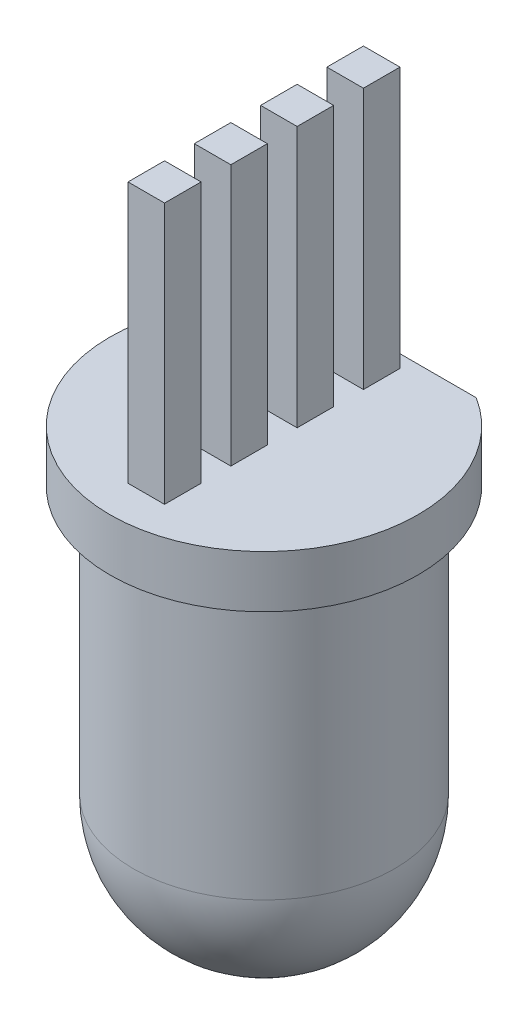
SolidWorks part; units mm, degrees
ref_plane "Plan de face" through (0, 0, 0) normal (0, 0, 1) x (1, 0, 0)
ref_plane "Plan de dessus" through (0, 0, 0) normal (0, 1, 0) x (1, 0, 0)
ref_plane "Plan de droite" through (0, 0, 0) normal (1, 0, 0) x (0, 0, -1)
sketch "Esquisse1" plane through (0, 0, 0) normal (0, 0, 1) x (1, 0, 0)
  line L0 (2.5, 7.6) -> (2.5, 2.5)
  line L1 (2.5, 7.6) -> (2.95, 7.6)
  line L2 (2.95, 7.6) -> (2.95, 8.6)
  line L3 (2.95, 8.6) -> (0, 8.6)
  line L4 (0, 0) -> (0, 10.615) construction
  line L5 (0, 0) -> (0, 8.6)
  arc A0 (2.5, 2.5) -> (0, 0) centre (0, 2.5) cw
  dimension "D1" = 2.5
  dimension "D2" = 7.6
  dimension "D3" = 90
  dimension "D4" = 0.45
  dimension "D5" = 1
  dimension "D6" = 5.9
revolve "Révolution1" add sketch "Esquisse1" angle 360 about L4
sketch "Esquisse2" plane through (0, 7.6, 0) normal (0, -1, 0) x (-1, 0, 0)
  line L0 (2.0316, 2.5) -> (-2.1192, 2.5)
  line L1 (2.0316, 2.5) -> (-0.3043, 5.4158)
  line L2 (-0.3043, 5.4158) -> (-2.1192, 2.5)
  circle A0 centre (0, 0) radius 2.5 construction
extrude "Enlèv. mat.-Extru.1" cut sketch "Esquisse2" against normal up to next
sketch "Esquisse3" plane through (0, 8.6, 0) normal (0, 1, 0) x (1, 0, 0)
  line L0 (-0.35, 2.255) -> (0.35, 2.255)
  line L1 (0.35, 2.255) -> (0.35, 1.555)
  line L2 (0.35, 1.555) -> (-0.35, 1.555)
  line L3 (-0.35, 1.555) -> (-0.35, 2.255)
  line L4 (-0.35, -0.985) -> (0.35, -0.985)
  line L5 (0.35, -0.985) -> (0.35, -0.285)
  line L6 (0.35, -0.285) -> (-0.35, -0.285)
  line L7 (-0.35, -0.285) -> (-0.35, -0.985)
  line L8 (-0.35, -1.555) -> (0.35, -1.555)
  line L9 (0.35, -1.555) -> (0.35, -2.255)
  line L10 (0.35, -2.255) -> (-0.35, -2.255)
  line L11 (-0.35, -2.255) -> (-0.35, -1.555)
  line L12 (-0.35, 0.985) -> (0.35, 0.985)
  line L13 (0.35, 0.985) -> (0.35, 0.285)
  line L14 (0.35, 0.285) -> (-0.35, 0.285)
  line L15 (-0.35, 0.285) -> (-0.35, 0.985)
  line L16 (0, 2.8041) -> (0, -3.2431) construction
  dimension "D1" = 0.7
  dimension "D2" = 0.7
  dimension "D3" = 0.35
  dimension "D4" = 0.35
  dimension "D5" = 0.35
  dimension "D6" = 0.7
  dimension "D7" = 0.7
  dimension "D8" = 0.7
  dimension "D9" = 0.7
  dimension "D10" = 0.35
  dimension "D11" = 1.27
  dimension "D12" = 0.7
  dimension "D13" = 0.7
  dimension "D14" = 1.27
  dimension "D15" = 1.27
  dimension "D16" = 0.285
extrude "Boss.-Extru.1" add sketch "Esquisse3" along normal blind 24.5
sketch "Esquisse4" plane through (-0.35, 0, 0) normal (-1, 0, 0) x (0, 0, 1)
  line L0 (-2.8851, 30.6) -> (-1.2657, 30.6)
  line L1 (-1.2657, 30.6) -> (-1.2657, 33.9219)
  line L2 (-1.2657, 33.9219) -> (0, 33.9219)
  line L3 (0, 33.9219) -> (0, 31.83)
  line L4 (0, 31.83) -> (1.3444, 31.83)
  line L5 (1.3444, 31.83) -> (1.3444, 30.6)
  line L6 (1.3444, 30.6) -> (2.8975, 30.6)
  line L7 (2.8975, 30.6) -> (2.8975, 34.6769)
  line L8 (2.8975, 34.6769) -> (-2.8851, 34.6769)
  line L9 (-2.8851, 34.6769) -> (-2.8851, 30.6)
  line L10 (-0.985, 33.1) -> (-0.285, 33.1) construction
  line L11 (0.285, 33.1) -> (0.985, 33.1) construction
  dimension "D1" = 2.5
  dimension "D2" = 2.5
  dimension "D3" = 1.27
extrude "Enlèv. mat.-Extru.2" cut sketch "Esquisse4" against normal up to next
sketch "Sketch1" plane through (-0.35, 0, 0) normal (-1, 0, 0) x (0, 0, 1)
  line L1 (2.255, 13.6) -> (-2.255, 13.6)
  line L2 (2.255, 13.6) -> (2.255, 33.1)
  line L3 (2.255, 33.1) -> (-2.255, 33.1)
  line L4 (-2.255, 13.6) -> (-2.255, 33.1)
  line L5 (2.255, 13.6) -> (-2.255, 33.1) construction
  line L6 (2.255, 33.1) -> (-2.255, 13.6) construction
  line L7 (-0.985, 33.1) -> (-0.285, 33.1) construction
  line L8 (2.255, 30.6) -> (2.255, 8.6) construction
  line L9 (-2.255, 30.6) -> (-2.255, 8.6) construction
  point P0 (0, 23.35)
  point P7 (0, 0)
  dimension "D1" = 19.5
extrude "Cut-Extrude1" cut sketch "Sketch1" against normal through all
